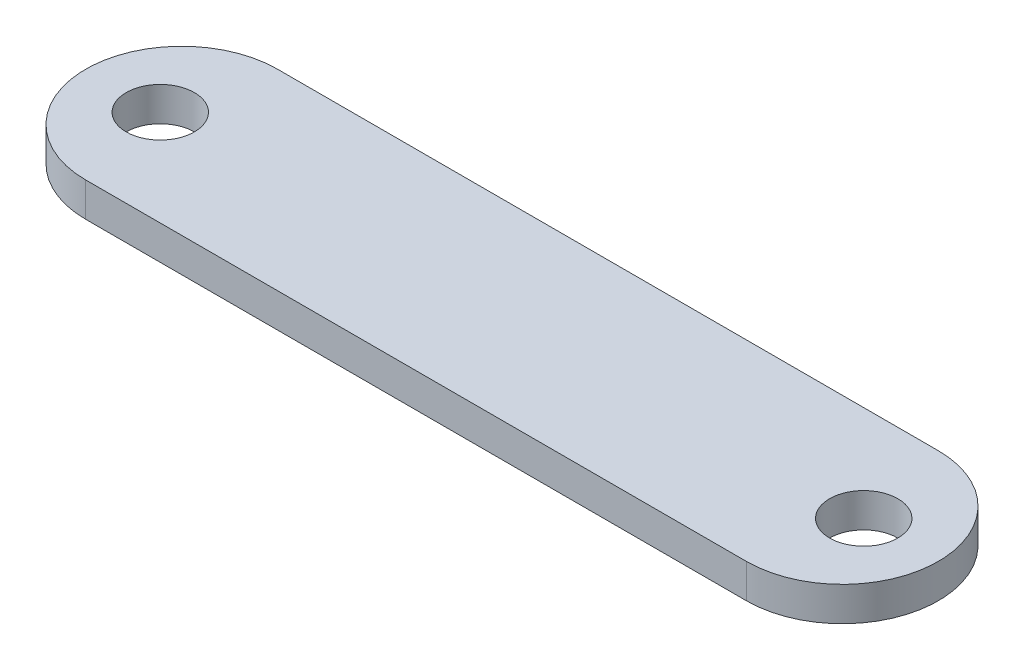
SolidWorks part; units mm, degrees
ref_plane "前视基准面" through (0, 0, 0) normal (0, 0, 1) x (1, 0, 0)
ref_plane "上视基准面" through (0, 0, 0) normal (0, 1, 0) x (1, 0, 0)
ref_plane "右视基准面" through (0, 0, 0) normal (1, 0, 0) x (0, 0, -1)
sketch "草图1" plane through (0, 0, 0) normal (0, 1, 0) x (1, 0, 0)
  line L0 (-15.5, 0) -> (15.5, 0) construction
  line L1 (-15.5, 4.5) -> (15.5, 4.5)
  line L2 (-15.5, -4.5) -> (15.5, -4.5)
  line L3 (-20, 6.3013) -> (-20, -6.3013) construction
  line L4 (20, 5.4798) -> (20, -5.4798) construction
  line L5 (0, 18.5133) -> (0, -18.5133) construction
  arc A0 (-15.5, 4.5) -> (-15.5, -4.5) centre (-15.5, 0) ccw
  arc A1 (15.5, -4.5) -> (15.5, 4.5) centre (15.5, 0) ccw
  circle A2 centre (-16.5, 0) radius 1.6
  circle A3 centre (16.5, 0) radius 1.6
  point P2 (0, 0)
  point P11 (-20, 0)
  point P14 (20, 0)
  point P19 (0, 0)
  dimension "D2" = 3.2
  dimension "D1" = 40
  dimension "D3" = 33
  dimension "D4" = 9
extrude "凸台-拉伸1" add sketch "草图1" along normal blind 1.6
